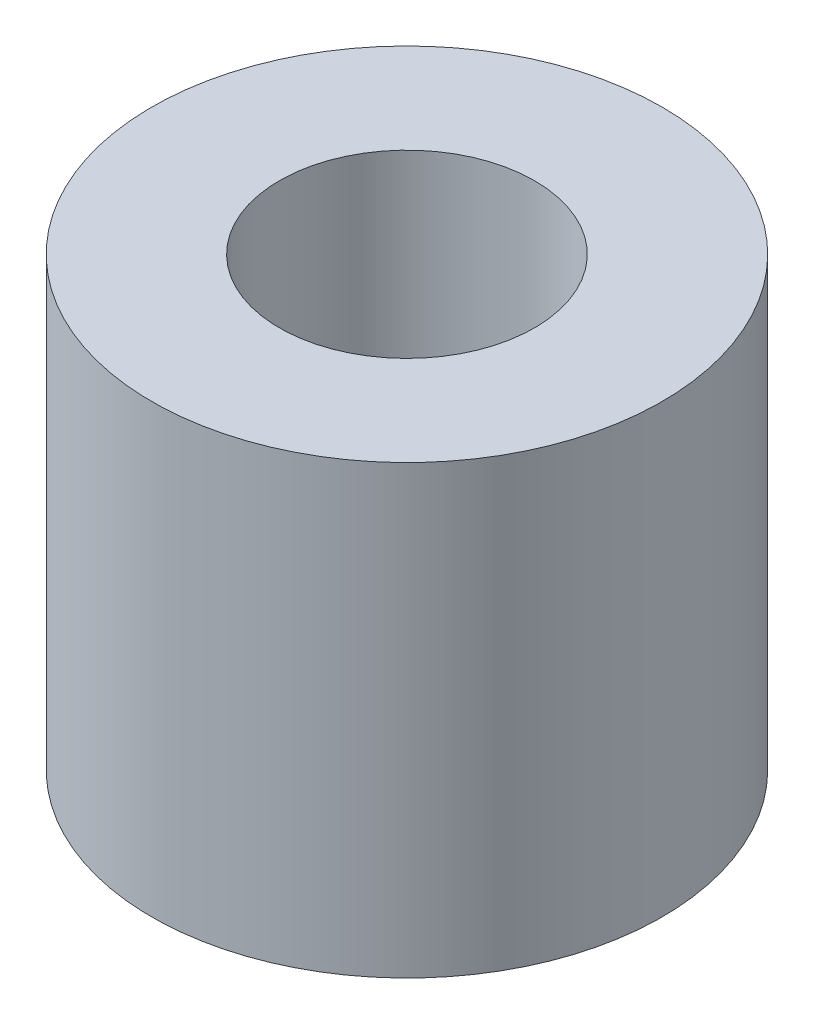
SolidWorks part; units mm, degrees
ref_plane "Front Plane" through (0, 0, 0) normal (0, 0, 1) x (1, 0, 0)
ref_plane "Top Plane" through (0, 0, 0) normal (0, 1, 0) x (1, 0, 0)
ref_plane "Right Plane" through (0, 0, 0) normal (1, 0, 0) x (0, 0, -1)
sketch "Sketch1" plane through (0, 0, 0) normal (0, 1, 0) x (1, 0, 0)
  circle A0 centre (0, 0) radius 1.5
  circle A1 centre (0, 0) radius 3
  dimension "D1" = 3
  dimension "D2" = 1.5
extrude "Boss-Extrude1" add sketch "Sketch1" along normal blind 5.25
